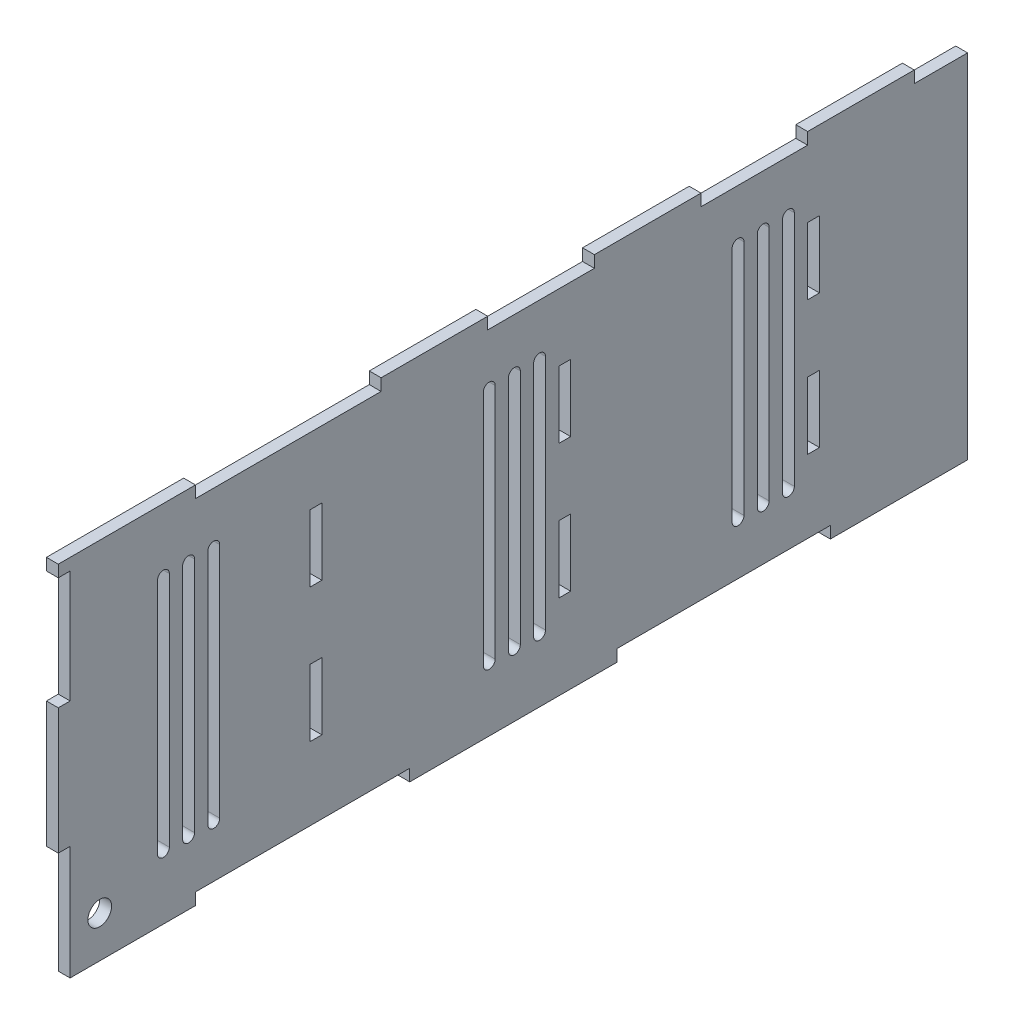
SolidWorks part; units mm, degrees
ref_plane "Front Plane" through (0, 0, 0) normal (0, 0, 1) x (1, 0, 0)
ref_plane "Top Plane" through (0, 0, 0) normal (0, 1, 0) x (1, 0, 0)
ref_plane "Right Plane" through (0, 0, 0) normal (1, 0, 0) x (0, 0, -1)
sketch "Sketch1" plane through (0, 0, 0) normal (1, 0, 0) x (0, 0, -1)
  line L1 (0, 0) -> (307, 0)
  line L2 (0, 0) -> (0, 115)
  line L3 (0, 115) -> (307, 115)
  line L4 (307, 0) -> (307, 115)
  dimension "D1" = 307
  dimension "D2" = 115
extrude "Boss-Extrude1" add sketch "Sketch1" along normal blind 4
sketch "Sketch2" plane through (4, 0, 0) normal (1, 0, 0) x (0, 0, -1)
  line L1 (0, 0) -> (46.3333, 0)
  line L2 (0, 0) -> (0, -4)
  line L3 (0, -4) -> (46.3333, -4)
  line L4 (46.3333, 0) -> (46.3333, -4)
  line L5 (307, 0) -> (260.6667, 0)
  line L6 (307, 0) -> (307, -4)
  line L7 (307, -4) -> (260.6667, -4)
  line L8 (260.6667, 0) -> (260.6667, -4)
  dimension "D1" = 46.3333
  dimension "D2" = 46.3333
  dimension "D3" = 4
extrude "Boss-Extrude2" add sketch "Sketch2" against normal blind 4
sketch "Sketch3" plane through (4, 0, 0) normal (1, 0, 0) x (0, 0, -1)
  line L1 (0, 115) -> (4, 115)
  line L2 (0, 115) -> (0, 77)
  line L3 (0, 77) -> (4, 77)
  line L4 (4, 115) -> (4, 77)
  line L5 (0, -4) -> (4, -4)
  line L6 (0, -4) -> (0, 34.5)
  line L7 (0, 34.5) -> (4, 34.5)
  line L8 (4, -4) -> (4, 34.5)
  line L9 (307, 115) -> (0, 115) construction
  dimension "D3" = 4
  dimension "D1" = 38
  dimension "D2" = 38.5
  dimension "D4" = 42.5
extrude "Cut-Extrude1" cut sketch "Sketch3" against normal blind 4
sketch "Sketch4" plane through (4, 0, 0) normal (1, 0, 0) x (0, 0, -1)
  line L0 (307, 115) -> (4, 115) construction
  line L1 (257, 92.4) -> (253, 92.4)
  line L2 (257, 92.4) -> (257, 69.8)
  line L3 (257, 69.8) -> (253, 69.8)
  line L4 (253, 92.4) -> (253, 69.8)
  line L5 (307, -4) -> (307, 115) construction
  line L6 (257, 47.2) -> (257, 24.6)
  line L7 (257, 47.2) -> (253, 47.2)
  line L8 (253, 47.2) -> (253, 24.6)
  line L9 (257, 24.6) -> (253, 24.6)
  dimension "D1" = 4
  dimension "D2" = 22.6
  dimension "D3" = 22.6
  dimension "D4" = 50
  dimension "D5" = 2
extrude "Cut-Extrude2" cut sketch "Sketch4" against normal through all
sketch "Sketch5" plane through (4, 0, 0) normal (1, 0, 0) x (0, 0, -1)
  line L0 (4, -4) -> (4, 34.5) construction
  line L1 (46.3333, 0) -> (260.6667, 0) construction
  circle A0 centre (14, 10) radius 4
  dimension "D1" = 8
  dimension "D2" = 10
  dimension "D3" = 10
extrude "Cut-Extrude3" cut sketch "Sketch5" against normal blind 4
pattern_linear "LPattern2" count 3 spacing 84 along (0, 0, 1) of "Cut-Extrude2"
sketch "Sketch6" plane through (0, 0, 0) normal (-1, 0, 0) x (0, 0, 1)
  line L0 (-46.3333, 0) -> (-260.6667, 0) construction
  line L1 (-188.6667, 0) -> (-118.6667, 0)
  line L2 (-188.6667, 0) -> (-188.6667, -4)
  line L3 (-188.6667, -4) -> (-118.6667, -4)
  line L4 (-118.6667, 0) -> (-118.6667, -4)
  line L5 (-260.6667, 0) -> (-260.6667, -4) construction
  point P6 (-153.6667, -4)
  dimension "D1" = 4
  dimension "D2" = 70
  dimension "D3" = 107
extrude "Boss-Extrude3" add sketch "Sketch6" against normal blind 4
pattern_linear "LPattern1" count 2 spacing 119 along (0, 1, 0) of "Boss-Extrude2"
sketch "Sketch7" plane through (4, 0, 0) normal (1, 0, 0) x (0, 0, -1)
  line L1 (307, 119) -> (289, 119)
  line L2 (307, 119) -> (307, 115)
  line L3 (307, 115) -> (289, 115)
  line L4 (289, 119) -> (289, 115)
  dimension "D1" = 18
  dimension "D2" = 4
extrude "Cut-Extrude4" cut sketch "Sketch7" against normal blind 4
sketch "Sketch8" plane through (4, 0, 0) normal (1, 0, 0) x (0, 0, -1)
  line L0 (260.6667, 115) -> (46.3333, 115) construction
  line L1 (289, 119) -> (253, 119)
  line L2 (289, 119) -> (289, 115)
  line L3 (289, 115) -> (253, 115)
  line L4 (253, 119) -> (253, 115)
  line L5 (217, 119) -> (217, 115)
  line L6 (217, 119) -> (181, 119)
  line L7 (181, 119) -> (181, 115)
  line L8 (217, 115) -> (181, 115)
  line L9 (145, 119) -> (145, 115)
  line L10 (145, 119) -> (109, 119)
  line L11 (109, 119) -> (109, 115)
  line L12 (145, 115) -> (109, 115)
  dimension "D1" = 36
  dimension "D2" = 3
extrude "Boss-Extrude5" add sketch "Sketch8" against normal blind 4
sketch "Sketch9" plane through (4, 0, 0) normal (1, 0, 0) x (0, 0, -1)
  line L0 (162.5, 97.5) -> (162.5, 17.5) construction
  line L1 (164.5, 97.5) -> (164.5, 17.5)
  line L2 (160.5, 97.5) -> (160.5, 17.5)
  line L3 (169, 69.3) -> (169, 92.9) construction
  line L4 (188.6667, -4) -> (118.6667, -4) construction
  line L5 (152, 97.5) -> (152, 17.5)
  line L6 (156, 97.5) -> (156, 17.5)
  line L7 (154, 97.5) -> (154, 17.5) construction
  line L8 (143.5, 97.5) -> (143.5, 17.5)
  line L9 (147.5, 97.5) -> (147.5, 17.5)
  line L10 (145.5, 97.5) -> (145.5, 17.5) construction
  arc A0 (164.5, 97.5) -> (160.5, 97.5) centre (162.5, 97.5) ccw
  arc A1 (160.5, 17.5) -> (164.5, 17.5) centre (162.5, 17.5) ccw
  arc A2 (156, 97.5) -> (152, 97.5) centre (154, 97.5) ccw
  arc A3 (152, 17.5) -> (156, 17.5) centre (154, 17.5) ccw
  arc A4 (147.5, 97.5) -> (143.5, 97.5) centre (145.5, 97.5) ccw
  arc A5 (143.5, 17.5) -> (147.5, 17.5) centre (145.5, 17.5) ccw
  point P2 (162.5, 57.5)
  point P14 (154, 57.5)
  point P21 (145.5, 57.5)
  dimension "D1" = 4
  dimension "D2" = 80
  dimension "D3" = 4.5
  dimension "D4" = 61.5
  dimension "D5" = 3
extrude "Cut-Extrude5" cut sketch "Sketch9" against normal blind 4
pattern_linear "LPattern3" count 3 spacing 84 along (0, 0, -1) of "Cut-Extrude5"
pattern_linear "LPattern4" count 2 spacing 110 along (0, 0, 1) of "Cut-Extrude5"
equation "\"Dikte\"= 4"
equation "\"D1@Sketch1\"=135+\"Dikte\"+34*2+50*2"
equation "\"D2@Sketch2\"=\"D1@Sketch2\""
equation "\"Tolerantie\"= 0.5"
equation "\"D1@Sketch3\"=39-2*\"Tolerantie\""
equation "\"D2@Sketch3\"=39-\"Tolerantie\""
